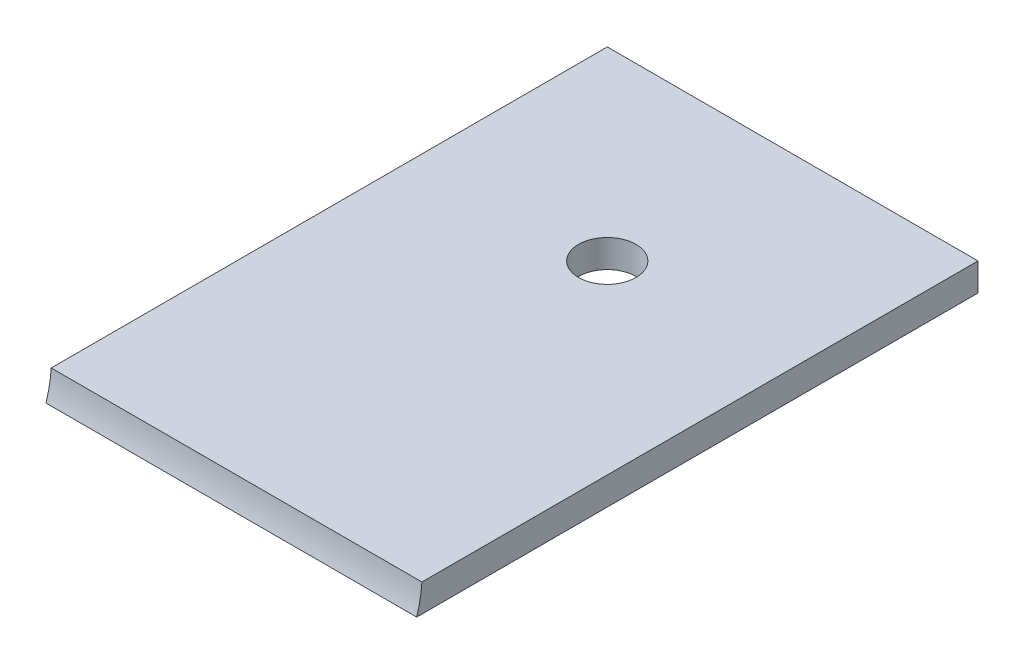
SolidWorks part; units mm, degrees
ref_plane "Front Plane" through (0, 0, 0) normal (0, 0, 1) x (1, 0, 0)
ref_plane "Top Plane" through (0, 0, 0) normal (0, 1, 0) x (1, 0, 0)
ref_plane "Right Plane" through (0, 0, 0) normal (1, 0, 0) x (0, 0, -1)
sketch "Sketch1" plane through (0, 0, 0) normal (0, 1, 0) x (1, 0, 0)
  line L0 (-20, -10) -> (20, -10) construction
  line L1 (-20, 30) -> (20, 30)
  line L2 (-20, 30) -> (-20, -30)
  line L3 (-20, -30) -> (20, -30)
  line L4 (20, 30) -> (20, -30)
  line L5 (-20, 30) -> (20, -30) construction
  line L6 (-20, -30) -> (20, 30) construction
  line L7 (20, -10) -> (-20, 30) construction
  circle A0 centre (0, 10) radius 3.1
  point P0 (0, 0)
  dimension "D4" = 6.2
  dimension "D1" = 40
  dimension "D2" = 60
  dimension "D3" = 20
extrude "Boss-Extrude1" add sketch "Sketch1" along normal blind 3
sketch "Sketch2" plane through (20, 0, 0) normal (1, 0, 0) x (0, 0, -1)
  circle A0 centre (-42.6732, 3.825) radius 12.7 construction
  circle A1 centre (-42.6732, 3.825) radius 12.7
sketch "Sketch3" plane through (20, 0, 0) normal (1, 0, 0) x (0, 0, -1)
  line L0 (-30, 0) -> (-30.5629, 0)
  line L1 (-30, 0) -> (-30, 3)
  circle A0 centre (-42.6732, 3.825) radius 12.7 construction
  arc A1 (-30.5629, 0) -> (-30, 3) centre (-42.6732, 3.825) ccw
extrude "Boss-Extrude2" add sketch "Sketch3" against normal up to surface (40 mm away) up to face at (-20, 1.5, 0)
